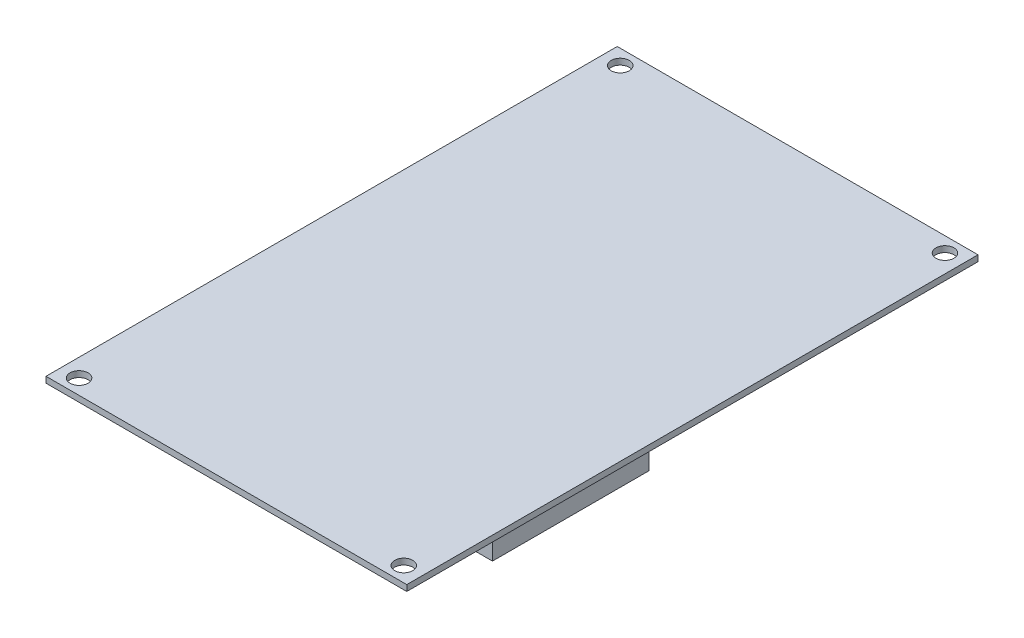
SolidWorks part; units mm, degrees
ref_plane "Front Plane" through (0, 0, 0) normal (0, 0, 1) x (1, 0, 0)
ref_plane "Top Plane" through (0, 0, 0) normal (0, 1, 0) x (1, 0, 0)
ref_plane "Right Plane" through (0, 0, 0) normal (1, 0, 0) x (0, 0, -1)
sketch "Sketch1" plane through (0, 0, 0) normal (0, 1, 0) x (1, 0, 0)
  line L1 (30, 47.5) -> (-30, 47.5)
  line L2 (30, 47.5) -> (30, -47.5)
  line L3 (30, -47.5) -> (-30, -47.5)
  line L4 (-30, 47.5) -> (-30, -47.5)
  line L5 (30, 47.5) -> (-30, -47.5) construction
  line L6 (30, -47.5) -> (-30, 47.5) construction
  point P0 (0, 0)
  dimension "D1" = 95
  dimension "D2" = 60
extrude "Boss-Extrude1" add sketch "Sketch1" along normal blind 1
sketch "Sketch2" plane through (0, 0, 0) normal (0, -1, 0) x (1, 0, 0)
  line L0 (0, 0) -> (0, -50000) construction
  line L1 (-30, 47.5) -> (30, 47.5) construction
  line L2 (24.25, 1.5) -> (19.25, 1.5)
  line L3 (24.25, 1.5) -> (24.25, 27.5)
  line L4 (24.25, 27.5) -> (19.25, 27.5)
  line L5 (19.25, 1.5) -> (19.25, 27.5)
  line L6 (-19.25, 1.5) -> (-24.25, 1.5)
  line L7 (-19.25, 1.5) -> (-19.25, 27.5)
  line L8 (-19.25, 27.5) -> (-24.25, 27.5)
  line L9 (-24.25, 1.5) -> (-24.25, 27.5)
  dimension "D1" = 5
  dimension "D2" = 38.5
  dimension "D3" = 26
  dimension "D4" = 20
extrude "Boss-Extrude2" add sketch "Sketch2" along normal blind 8.5
sketch "Sketch3" plane through (0, 1, 0) normal (0, 1, 0) x (1, 0, 0)
  line L0 (0, 0) -> (0, 50000) construction
  line L1 (0, 0) -> (50000, 0) construction
  circle A0 centre (-27, -45) radius 1.5
  circle A1 centre (27, -45) radius 1.5
  circle A2 centre (27, 45) radius 1.5
  circle A3 centre (-27, 45) radius 1.5
  dimension "D1" = 3
  dimension "D2" = 54
  dimension "D3" = 90
extrude "Cut-Extrude1" cut sketch "Sketch3" against normal up to next
